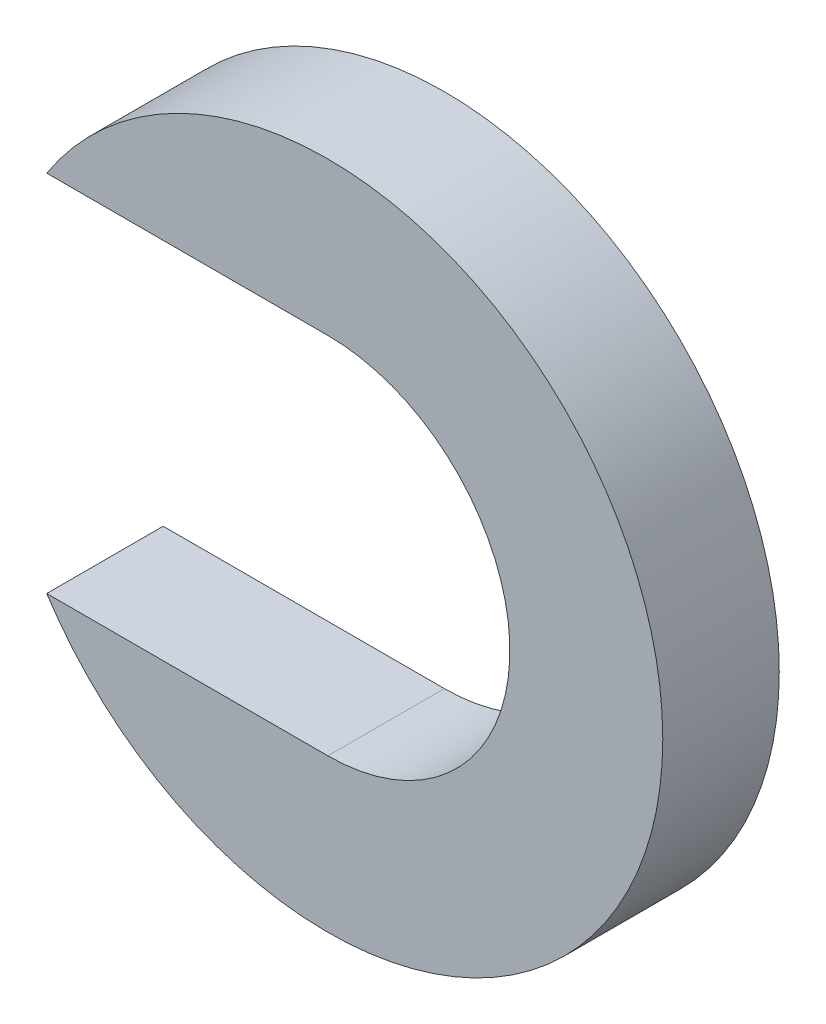
SolidWorks part; units mm, degrees
material "AISI 1020 Acero laminado en frío"
ref_plane "Alzado" through (0, 0, 0) normal (0, 0, 1) x (1, 0, 0)
ref_plane "Planta" through (0, 0, 0) normal (0, 1, 0) x (1, 0, 0)
ref_plane "Vista lateral" through (0, 0, 0) normal (1, 0, 0) x (0, 0, -1)
sketch "Croquis1" plane through (0, 0, 0) normal (0, 0, 1) x (1, 0, 0)
  circle A0 centre (0, 0) radius 9.1281
  dimension "D1" = 18.2562
extrude "Saliente-Extruir1" add sketch "Croquis1" along normal blind 3.175
sketch "Croquis4" plane through (0, 0, 3.175) normal (0, 0, 1) x (1, 0, 0)
  line L0 (0, 4.9609) -> (-7.6624, 4.9609)
  line L1 (0, -4.9609) -> (-7.6624, -4.9609)
  arc A0 (0, -4.9609) -> (0, 4.9609) centre (0, 0) ccw
  circle A1 centre (0, 0) radius 9.1281 construction
  arc A2 (-7.6624, -4.9609) -> (-7.6624, 4.9609) centre (0, 0) cw
  dimension "D1" = 9.9219
extrude "Cortar-Extruir1" cut sketch "Croquis4" against normal through all
